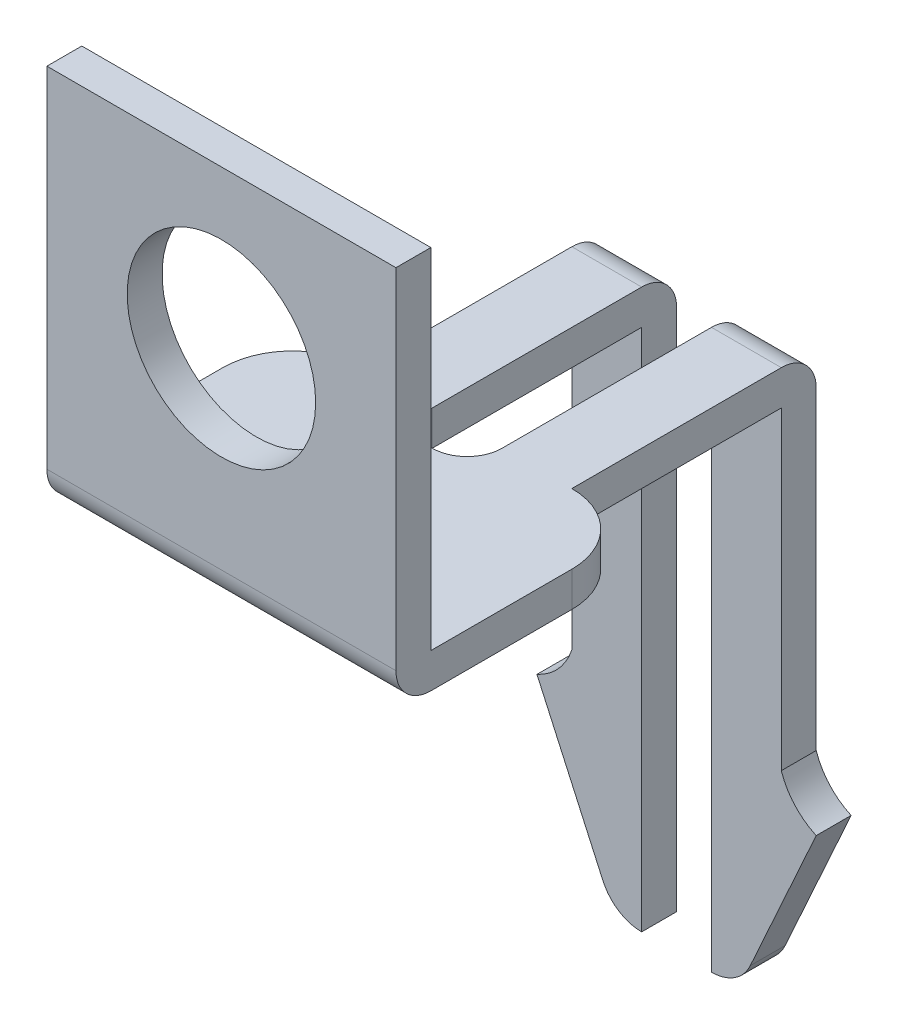
SolidWorks part; units mm, degrees
material "Cobre"
ref_plane "Plano frontal" through (0, 0, 0) normal (0, 0, 1) x (1, 0, 0)
ref_plane "Plano superior" through (0, 0, 0) normal (0, 1, 0) x (1, 0, 0)
ref_plane "Plano direito" through (0, 0, 0) normal (1, 0, 0) x (0, 0, -1)
sketch "Esboço1" plane through (0, 0, 0) normal (0, 0, 1) x (1, 0, 0)
  line L0 (0, 0) -> (2.5, 0) construction
  line L1 (-2.5, 2.75) -> (2.5, 2.75)
  line L2 (-2.5, 2.75) -> (-2.5, -2.75)
  line L3 (-2.5, -2.75) -> (2.5, -2.75)
  line L4 (2.5, 2.75) -> (2.5, -2.75)
  line L5 (0, 0) -> (0, 2.75) construction
  line L6 (0, 0.5) -> (0, 0) construction
  circle A0 centre (0, 0.5) radius 1.35
  dimension "D3" = 2.7
  dimension "D1" = 5.5
  dimension "D2" = 5
  dimension "D4" = 3.25
extrude "Ressalto-extrusão1" add sketch "Esboço1" against normal blind 0.5
sketch "Esboço2" plane through (0, 0, -0.5) normal (0, 0, -1) x (-1, 0, 0)
  line L0 (2.5, 2.75) -> (2.5, -2.75) construction
  line L1 (-2.5, -2.75) -> (2.5, -2.75)
  line L2 (-2.5, -2.75) -> (-2.5, -2.25)
  line L3 (-2.5, -2.25) -> (2.5, -2.25)
  line L4 (2.5, -2.75) -> (2.5, -2.25)
  dimension "D1" = 0.5
extrude "Ressalto-extrusão2" add sketch "Esboço2" along normal blind 6.52
fillet "Filete3" radius 0.5 1 edges at (0, -2.75, 0)
sketch "Esboço3" plane through (0, -2.25, 0) normal (0, 1, 0) x (1, 0, 0)
  line L0 (-0.5, 7.02) -> (-0.5, 3.52)
  line L1 (-2.5, 7.02) -> (2.5, 7.02) construction
  line L2 (0.5, 3.52) -> (0.5, 7.02)
  line L3 (0.5, 7.02) -> (-0.5, 7.02)
  line L4 (0, 7.02) -> (0, 0.5) construction
  line L5 (-2.5, 0.5) -> (2.5, 0.5) construction
  arc A0 (-0.5, 3.52) -> (0.5, 3.52) centre (0, 3.52) ccw
  dimension "D1" = 1
  dimension "D2" = 3.5
extrude "Corte-extrusão1" cut sketch "Esboço3" against normal through all
sketch "Esboço4" plane through (0, -2.25, 0) normal (0, 1, 0) x (1, 0, 0)
  line L0 (1.5, 7.02) -> (1.5, 3.52)
  line L3 (2.5, 2.52) -> (2.5, 7.02)
  line L4 (2.5, 7.02) -> (1.5, 7.02)
  line L6 (0.5, 3.52) -> (0.5, 7.02) construction
  arc A0 (1.5, 3.52) -> (2.5, 2.52) centre (1.5, 2.52) cw
  dimension "D1" = 1
  dimension "D2" = 3.5
extrude "Corte-extrusão2" cut sketch "Esboço4" against normal through all
mirror "Espelhar1" about plane through (0, 0, 0) normal (1, 0, 0) of "Corte-extrusão2"
sketch "Esboço5" plane through (0, -2.75, 0) normal (0, -1, 0) x (1, 0, 0)
  line L0 (-0.5, -7.02) -> (-0.5, -3.52) construction
  line L1 (-1.5, -7.02) -> (-0.5, -7.02)
  line L2 (-1.5, -7.02) -> (-1.5, -6.52)
  line L3 (-1.5, -6.52) -> (-0.5, -6.52)
  line L4 (-0.5, -7.02) -> (-0.5, -6.52)
  dimension "D1" = 0.5
extrude "Ressalto-extrusão3" add sketch "Esboço5" along normal blind 7.5
fillet "Filete4" radius 0.5 1 edges at (-1, -2.25, -7.02)
sketch "Esboço6" plane through (0, 0, -7.02) normal (0, 0, -1) x (-1, 0, 0)
  line L1 (0.5, -10.25) -> (2.02, -10.25)
  line L2 (0.5, -10.25) -> (0.5, -7.25)
  line L3 (0.5, -7.25) -> (2.02, -7.25)
  line L4 (2.02, -10.25) -> (2.02, -7.25)
  dimension "D1" = 3
  dimension "D2" = 1.52
extrude "Ressalto-extrusão4" add sketch "Esboço6" against normal blind 0.5
sketch "Esboço7" plane through (0, 0, -7.02) normal (0, 0, -1) x (-1, 0, 0)
  line L0 (1.5, -7.25) -> (2.02, -7.25)
  line L1 (2.02, -7.25) -> (2.02, -10.25)
  line L2 (2.02, -10.25) -> (0.5, -10.25)
  line L3 (1.0551, -9.892) -> (2, -7.8051)
  line L4 (1.5, -7.25) -> (1.5, -2.75) construction
  arc A0 (0.5, -10.25) -> (1.0551, -9.892) centre (0.5, -9.6407) ccw
  arc A1 (2, -7.8051) -> (1.5, -7.25) centre (2.3844, -6.9561) cw
  point P12 (0, 0)
  dimension "D1" = 0.5551
  dimension "D2" = 0.5551
  dimension "D3" = 0.5
extrude "Corte-extrusão3" cut sketch "Esboço7" against normal through all
mirror "Espelhar2" about plane through (0, 0, 0) normal (1, 0, 0) of "Corte-extrusão3", "Ressalto-extrusão4", "Filete4", "Ressalto-extrusão3"
